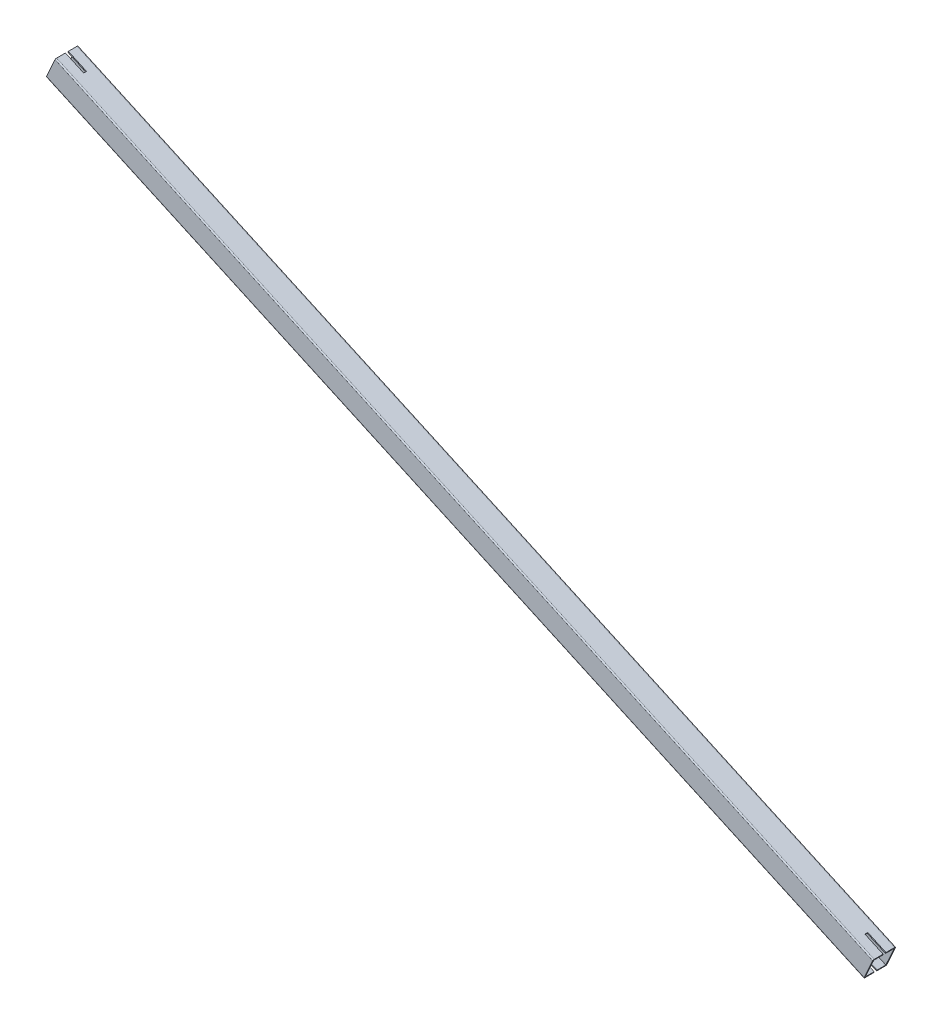
SolidWorks part; units mm, degrees
material "Простая углеродистая сталь"
ref_plane "Спереди" through (0, 0, 0) normal (0, 0, 1) x (1, 0, 0)
ref_plane "Сверху" through (0, 0, 0) normal (0, 1, 0) x (1, 0, 0)
ref_plane "Справа" through (0, 0, 0) normal (1, 0, 0) x (0, 0, -1)
sketch "Эскиз1" plane through (0, 0, 0) normal (0, 0, 1) x (1, 0, 0)
  line L0 (0, 0) -> (2867.6544, -1303.4793)
  line L1 (0, 0) -> (5735.3088, 0) construction
  line L2 (0, 0) -> (0, -2606.9585) construction
  line L3 (0, -2606.9585) -> (5735.3088, -2606.9585) construction
  line L4 (5735.3088, 0) -> (5735.3088, -2606.9585) construction
  line L5 (5735.3088, 0) -> (0, -2606.9585) construction
  line L6 (5735.3088, -2606.9585) -> (0, 0) construction
  dimension "D1" = 3150
  dimension "D2" = 65.556
other "Квадратная труба гост 8639-82 _80 X 80 X 4.0(1)"
ref_plane "Плоскость1" through (0, 0, 0) normal (0.9104, -0.4138, 0) x (0.4138, 0.9104, 0)
sketch "Sketch11" plane through (0, 0, 0) normal (0.9104, -0.4138, 0) x (0.4138, 0.9104, 0)
  line L0 (-35.999, -36) -> (35.999, -36)
  line L1 (-36, -35.999) -> (-36, 35.999)
  line L2 (35.999, 36) -> (-35.999, 36)
  line L3 (36, 35.999) -> (36, -35.999)
  line L4 (-35.999, -40) -> (35.999, -40)
  line L5 (-40, -35.999) -> (-40, 35.999)
  line L6 (35.999, 40) -> (-35.999, 40)
  line L7 (40, 35.999) -> (40, -35.999)
  arc A0 (40, 35.999) -> (35.999, 40) centre (35.999, 35.999) ccw
  arc A1 (35.999, -40) -> (40, -35.999) centre (35.999, -35.999) ccw
  arc A2 (-40, -35.999) -> (-35.999, -40) centre (-35.999, -35.999) ccw
  arc A3 (-35.999, 40) -> (-40, 35.999) centre (-35.999, 35.999) ccw
  arc A4 (-35.999, 36) -> (-36, 35.999) centre (-35.999, 35.999) ccw
  arc A5 (36, 35.999) -> (35.999, 36) centre (35.999, 35.999) ccw
  arc A6 (35.999, -36) -> (36, -35.999) centre (35.999, -35.999) ccw
  arc A7 (-36, -35.999) -> (-35.999, -36) centre (-35.999, -35.999) ccw
  point P0 (-40, 0)
  point P1 (40, 0)
  point P2 (0, 40)
  point P3 (0, -40)
  point P4 (0, 0)
  point P5 (-40, -40)
  point P6 (40, -40)
  point P7 (40, 40)
  point P8 (-40, 40)
  point P33 (0, 0)
  dimension "D1" = 4.001
  dimension "Thickness" = 4
  dimension "V_leg" = 80
sketch "Эскиз3" plane through (-16.5521, -36.4147, 0) normal (-0.4138, -0.9104, 0) x (0.9104, -0.4138, 0)
  line L0 (0, 0) -> (40.9414, 0) construction
  line L1 (0, 35.999) -> (0, -35.999) construction
  line L2 (0, 5) -> (70, 5)
  line L3 (0, 5) -> (0, -5)
  line L4 (0, -5) -> (70, -5)
  line L5 (70, 5) -> (70, -5)
  line L6 (3150, 0) -> (4923.0006, 0) construction
  line L7 (3150, 35.999) -> (3150, -35.999) construction
  line L9 (3150, 5) -> (3080, 5)
  line L10 (3150, 5) -> (3150, -5)
  line L11 (3150, -5) -> (3080, -5)
  line L12 (3080, 5) -> (3080, -5)
  dimension "D1" = 70
  dimension "D2" = 10
extrude "Вырез-Вытянуть1" cut sketch "Эскиз3" against normal through all
sketch "Эскиз4" [suppressed] plane through (1426.9754, -1934.8819, -2404.1686) normal (-0.5935, 0.8048, 0) x (-0.6477, -0.4777, -0.5935)
  line L0 (0, 0) -> (40.9414, 0) construction
  line L2 (0, 3) -> (40, 3)
  line L3 (0, 3) -> (0, -3)
  line L4 (0, -3) -> (40, -3)
  line L5 (40, 3) -> (40, -3)
  line L6 (4970.161, 0) -> (4923.0006, 0) construction
  line L9 (4970.161, 3) -> (4930.161, 3)
  line L10 (4970.161, 3) -> (4970.161, -3)
  line L11 (4970.161, -3) -> (4930.161, -3)
  line L12 (4930.161, 3) -> (4930.161, -3)
  dimension "D1" = 40
  dimension "D2" = 6
equation "\"D1@Sketch11\" = \"Thickness@Sketch11\"+0.001"
